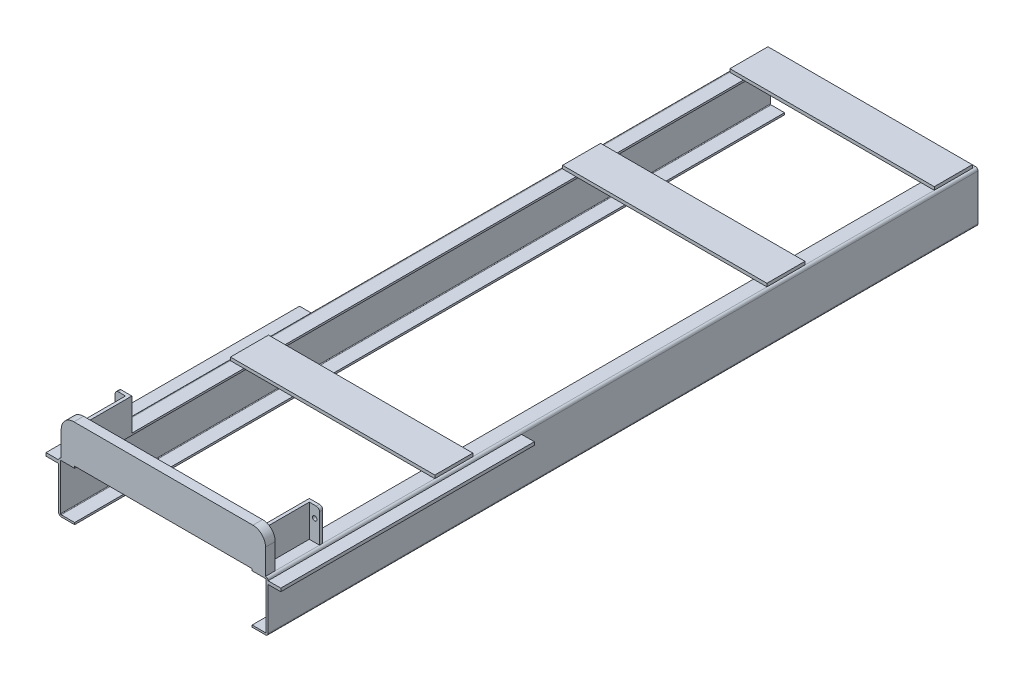
SolidWorks part; units mm, degrees
ref_plane "Front Plane" through (0, 0, 0) normal (0, 0, 1) x (1, 0, 0)
ref_plane "Top Plane" through (0, 0, 0) normal (0, 1, 0) x (1, 0, 0)
ref_plane "Right Plane" through (0, 0, 0) normal (1, 0, 0) x (0, 0, -1)
sketch "Sketch1" plane through (0, 0, 0) normal (0, 0, 1) x (1, 0, 0)
  line L0 (0, 0) -> (413, 0) construction
  line L1 (350, 100) -> (403, 100)
  line L2 (413, 90) -> (413, -90)
  line L3 (403, -100) -> (350, -100)
  arc A0 (413, -90) -> (403, -100) centre (403, -90) cw
  arc A1 (403, 100) -> (413, 90) centre (403, 90) cw
  point P5 (413, 0)
  point P10 (413, -100)
  point P13 (413, 100)
  dimension "D4" = 10
  dimension "D1" = 200
  dimension "D2" = 413
  dimension "D3" = 63
extrude "Extrude-Thin1" add sketch "Sketch1" along normal mid plane 2800 thin
sketch "Sketch2" plane through (0, 0, 1400) normal (0, 0, 1) x (1, 0, 0)
  line L1 (413, 90) -> (463, 90)
  line L2 (413, 90) -> (413, 77.5)
  line L3 (413, 77.5) -> (463, 77.5)
  line L4 (463, 90) -> (463, 77.5)
  dimension "D1" = 50
  dimension "D2" = 12.5
extrude "Boss-Extrude1" add sketch "Sketch2" against normal blind 1000
mirror "Mirror2" about plane through (0, 0, 0) normal (1, 0, 0) of bodies 102
sketch "Sketch3" plane through (0, 0, 1400) normal (0, 0, 1) x (1, 0, 0)
  line L5 (-403, 100) -> (403, 100)
  line L6 (-403, 100) -> (-403, 200)
  line L7 (-353, 250) -> (353, 250)
  line L8 (403, 100) -> (403, 200)
  arc A0 (-403, 200) -> (-353, 250) centre (-353, 200) cw
  arc A1 (353, 250) -> (403, 200) centre (353, 200) cw
  point P4 (0, 0)
  point P5 (0, 0)
  point P15 (403, 250)
  dimension "D2" = 50
  dimension "D1" = 150
extrude "Boss-Extrude2" add sketch "Sketch3" against normal blind 38
sketch "Sketch4" plane through (0, 100, 0) normal (0, 1, 0) x (1, 0, 0)
  line L0 (-403, -1362) -> (-403, 1400) construction
  line L1 (-403, 1387.5) -> (403, 1387.5)
  line L2 (-403, 1387.5) -> (-403, 1237.5)
  line L3 (-403, 1237.5) -> (403, 1237.5)
  line L4 (403, 1387.5) -> (403, 1237.5)
  line L5 (403, -1362) -> (403, 1400) construction
  line L8 (350, 1400) -> (403, 1400) construction
  dimension "D1" = 12.5
  dimension "D2" = 150
extrude "Boss-Extrude3" add sketch "Sketch4" along normal blind 12.5
pattern_linear "LPattern1" count 2 spacing 660 along (0, 0, 1) of "Boss-Extrude3"
pattern_linear "LPattern2" count 2 spacing 1970 along (0, 0, 1) of "Boss-Extrude3"
sketch "Sketch5" plane through (0, 0, 1362) normal (0, 0, -1) x (-1, 0, 0)
  line L1 (-350, 100) -> (-362.5, 100)
  line L2 (-350, 100) -> (-350, 227)
  line L3 (-350, 227) -> (-362.5, 227)
  line L4 (-362.5, 100) -> (-362.5, 227)
  dimension "D1" = 127
  dimension "D2" = 12.5
extrude "Boss-Extrude4" add sketch "Sketch5" along normal blind 175
sketch "Sketch6" plane through (0, 0, 1187) normal (0, 0, -1) x (-1, 0, 0)
  line L0 (-350, 227) -> (-362.5, 227) construction
  line L1 (-350, 100) -> (-403, 100)
  line L2 (-350, 100) -> (-350, 227)
  line L3 (-350, 227) -> (-403, 227)
  line L4 (-403, 100) -> (-403, 227)
  circle A0 centre (-384, 182) radius 8.75
  dimension "D1" = 17.5
  dimension "D2" = 82
  dimension "D3" = 19
extrude "Boss-Extrude5" add sketch "Sketch6" along normal blind 12.5
fillet "Fillet1" radius 12.5 1 edges at (403, 227, 1180.75)
mirror "Mirror3" about plane through (0, 0, 0) normal (1, 0, 0) of "Fillet1", "Boss-Extrude4", "Boss-Extrude5"
